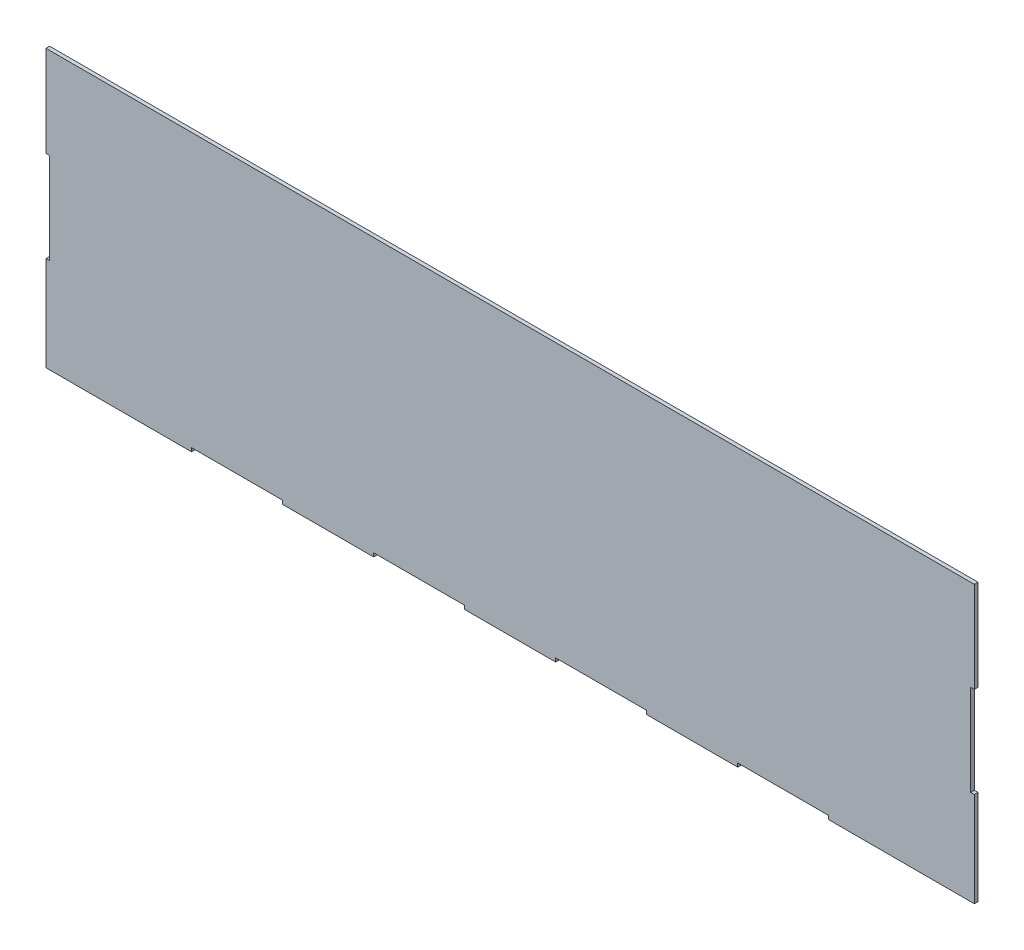
SolidWorks part; units mm, degrees
ref_plane "前视基准面" through (0, 0, 0) normal (0, 0, 1) x (1, 0, 0)
ref_plane "上视基准面" through (0, 0, 0) normal (0, 1, 0) x (1, 0, 0)
ref_plane "右视基准面" through (0, 0, 0) normal (1, 0, 0) x (0, 0, -1)
other "Configuration Table"
sketch "草图1" plane through (0, 0, 0) normal (0, 0, 1) x (1, 0, 0)
  line L0 (878.9995, 804.9663) -> (874.9995, 804.9663)
  line L1 (878.9995, 904.9663) -> (878.9995, 804.9663)
  line L2 (874.9995, 904.9663) -> (878.9995, 904.9663)
  line L3 (874.9995, 1004.9663) -> (874.9995, 904.9663)
  line L4 (1894.9995, 904.9663) -> (1894.9995, 1004.9663)
  line L5 (1890.9995, 904.9663) -> (1894.9995, 904.9663)
  line L6 (1890.9995, 804.9663) -> (1890.9995, 904.9663)
  line L7 (1894.9995, 804.9663) -> (1890.9995, 804.9663)
  line L8 (1894.9995, 700.9663) -> (1894.9995, 804.9663)
  line L9 (1734.9995, 700.9663) -> (1894.9995, 700.9663)
  line L10 (1734.9995, 704.9663) -> (1734.9995, 700.9663)
  line L11 (1634.9995, 704.9663) -> (1734.9995, 704.9663)
  line L12 (1634.9995, 700.9663) -> (1634.9995, 704.9663)
  line L13 (1534.9995, 700.9663) -> (1634.9995, 700.9663)
  line L14 (1534.9995, 704.9663) -> (1534.9995, 700.9663)
  line L15 (1434.9995, 704.9663) -> (1534.9995, 704.9663)
  line L16 (1434.9995, 700.9663) -> (1434.9995, 704.9663)
  line L17 (1334.9995, 700.9663) -> (1434.9995, 700.9663)
  line L18 (1334.9995, 704.9663) -> (1334.9995, 700.9663)
  line L19 (1234.9995, 704.9663) -> (1334.9995, 704.9663)
  line L20 (1234.9995, 700.9663) -> (1234.9995, 704.9663)
  line L21 (1134.9995, 700.9663) -> (1234.9995, 700.9663)
  line L22 (1134.9995, 704.9663) -> (1134.9995, 700.9663)
  line L23 (1034.9995, 704.9663) -> (1134.9995, 704.9663)
  line L24 (1034.9995, 700.9663) -> (1034.9995, 704.9663)
  line L25 (874.9995, 700.9663) -> (1034.9995, 700.9663)
  line L26 (874.9995, 804.9663) -> (874.9995, 700.9663)
  line L27 (874.9995, 1004.9663) -> (1894.9995, 1004.9663)
extrude "凸台-拉伸1" add sketch "草图1" along normal blind 4
